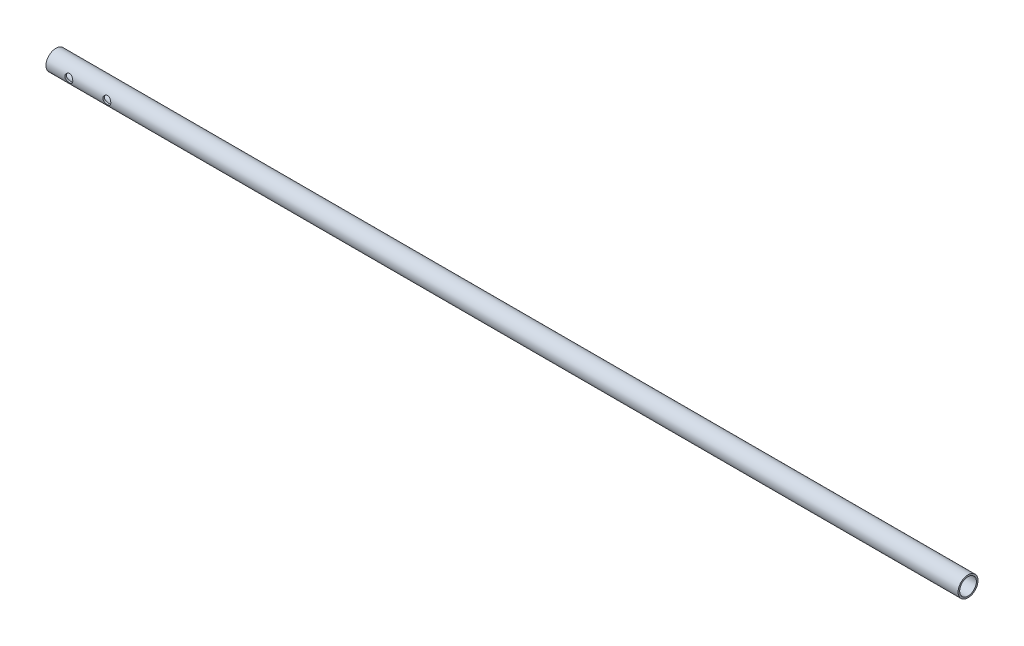
SolidWorks part; units mm, degrees
material "Thornel VCB-20 Carbon Cloth"
ref_plane "Front Plane" through (0, 0, 0) normal (0, 0, 1) x (1, 0, 0)
ref_plane "Top Plane" through (0, 0, 0) normal (0, 1, 0) x (1, 0, 0)
ref_plane "Right Plane" through (0, 0, 0) normal (1, 0, 0) x (0, 0, -1)
sketch "Sketch1" plane through (0, 0, 0) normal (1, 0, 0) x (0, 0, -1)
  circle A0 centre (0, 0) radius 6.55
  circle A1 centre (0, 0) radius 5.5
  dimension "D1" = 13.1
  dimension "D2" = 11
extrude "Boss-Extrude1" add sketch "Sketch1" along normal blind 600
sketch "Sketch3" plane through (0, 0, 0) normal (0, 0, 1) x (1, 0, 0)
  line L0 (0, 0) -> (600, 0) construction
  line L1 (600, -6.55) -> (600, 6.55) construction
  line L2 (0, 6.55) -> (0, -6.55) construction
  circle A0 centre (15, 0) radius 2.625
  circle A1 centre (40, 0) radius 2.625
  dimension "D2" = 5.25
  dimension "D4" = 5.25
  dimension "D1" = 15
  dimension "D3" = 25
extrude "Cut-Extrude1" cut sketch "Sketch3" against normal through all both and the other way through all
